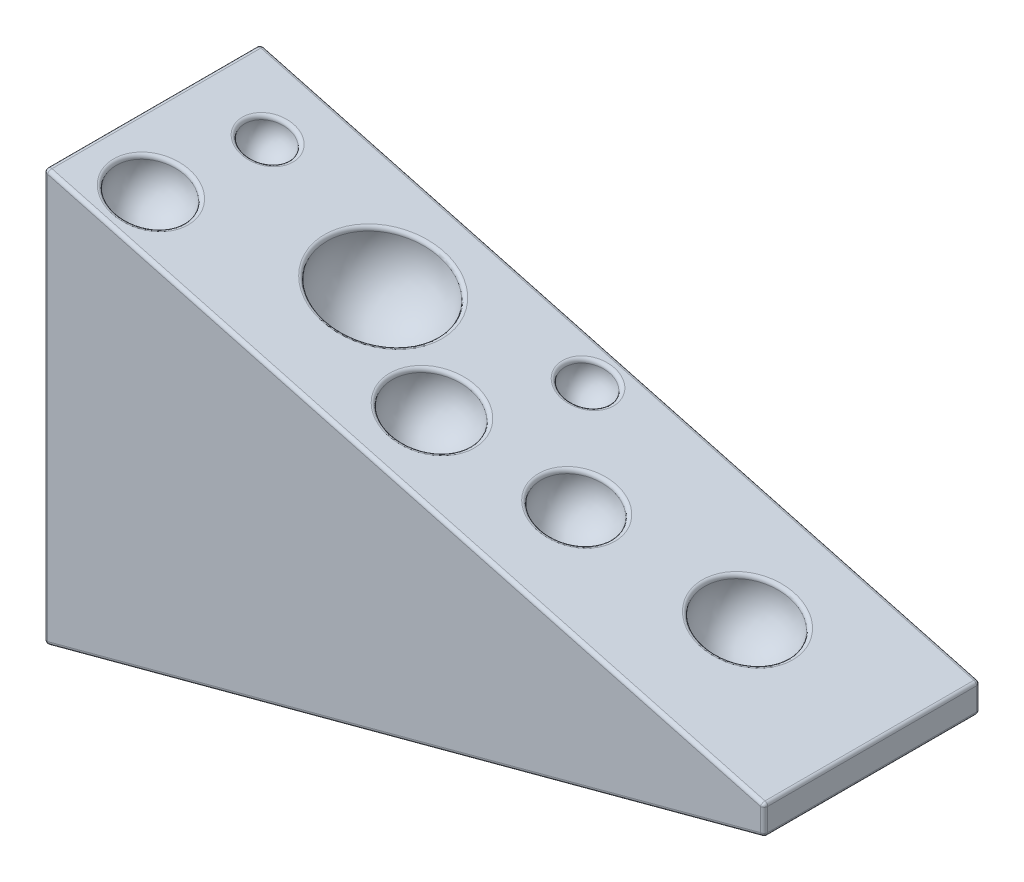
SolidWorks part; units mm, degrees
ref_plane "Front Plane" through (0, 0, 0) normal (0, 0, 1) x (1, 0, 0)
ref_plane "Top Plane" through (0, 0, 0) normal (0, 1, 0) x (1, 0, 0)
ref_plane "Right Plane" through (0, 0, 0) normal (1, 0, 0) x (0, 0, -1)
sketch "Sketch1" plane through (0, 0, 0) normal (0, 0, 1) x (1, 0, 0)
  line L0 (-975.3379, 57.5) -> (49024.6621, 57.5) construction
  line L1 (0, 0) -> (200, 53.5898)
  line L2 (0, 0) -> (0, 115)
  line L3 (0, 115) -> (200, 61.4102)
  line L4 (200, 53.5898) -> (200, 61.4102)
  point P7 (200, 57.5)
  dimension "D1" = 200
  dimension "D2" = 30
  dimension "D3" = 115
  dimension "D4" = 57.5
extrude "Boss-Extrude1" add sketch "Sketch1" along normal blind 60
sketch "Sketch2" plane through (0, 0, 0) normal (0.2588, -0.9659, 0) x (0.9659, 0.2588, 0)
  line L0 (117.0552, 35) -> (137.0552, 35) construction
  line L1 (0, 60) -> (207.0552, 60) construction
  line L2 (207.0552, 60) -> (207.0552, 0) construction
  line L3 (117.0552, 35) -> (137.0552, 35)
  arc A0 (137.0552, 35) -> (117.0552, 35) centre (127.0552, 35) ccw
  dimension "D1" = 10
  dimension "D2" = 25
  dimension "D3" = 80
revolve "Cut-Revolve1" cut sketch "Sketch2" angle 360 about L0
sketch "Sketch4" plane through (0, 0, 0) normal (0.2588, -0.9659, 0) x (0.9659, 0.2588, 0)
  line L0 (7.0994, 46.7676) -> (26.5364, 46.7676)
  arc A0 (26.5364, 46.7676) -> (7.0994, 46.7676) centre (16.8179, 46.7676) ccw
revolve "Cut-Revolve2" cut sketch "Sketch4" angle 360 about L0
sketch "Sketch5" plane through (0, 0, 0) normal (0.2588, -0.9659, 0) x (0.9659, 0.2588, 0)
  line L0 (45.8757, 25.6804) -> (77.6549, 25.6804)
  arc A0 (77.6549, 25.6804) -> (45.8757, 25.6804) centre (61.7653, 25.6804) ccw
revolve "Cut-Revolve3" cut sketch "Sketch5" angle 360 about L0
sketch "Sketch6" plane through (0, 0, 0) normal (0.2588, -0.9659, 0) x (0.9659, 0.2588, 0)
  line L0 (156.4971, 27.6063) -> (180.4971, 27.6063)
  arc A0 (180.4971, 27.6063) -> (156.4971, 27.6063) centre (168.4971, 27.6063) ccw
  dimension "D1" = 24
revolve "Cut-Revolve4" cut sketch "Sketch6" angle 360 about L0
sketch "Sketch7" plane through (0, 0, 0) normal (0.2588, -0.9659, 0) x (0.9659, 0.2588, 0)
  line L0 (13.4951, 17.2284) -> (26.0888, 17.2284)
  arc A0 (26.0888, 17.2284) -> (13.4951, 17.2284) centre (19.7919, 17.2284) ccw
revolve "Cut-Revolve5" cut sketch "Sketch7" angle 360 about L0
sketch "Sketch8" plane through (0, 0, 0) normal (0.2588, -0.9659, 0) x (0.9659, 0.2588, 0)
  line L0 (97.5898, 9.5515) -> (110.3086, 9.5515)
  arc A0 (110.3086, 9.5515) -> (97.5898, 9.5515) centre (103.9492, 9.5515) ccw
revolve "Cut-Revolve6" cut sketch "Sketch8" angle 360 about L0
sketch "Sketch9" plane through (0, 0, 0) normal (0.2588, -0.9659, 0) x (0.9659, 0.2588, 0)
  line L0 (80.4765, 40.977) -> (102.7844, 40.977)
  arc A0 (102.7844, 40.977) -> (80.4765, 40.977) centre (91.6305, 40.977) ccw
revolve "Cut-Revolve7" cut sketch "Sketch9" angle 360 about L0
ref_plane "Plane1" through (0, 57, 0) normal (0, 1, 0) x (1, 0, 0)
mirror "Mirror2" about plane through (0, 57, 0) normal (0, 1, 0) of "Cut-Revolve7", "Cut-Revolve6", "Cut-Revolve5", "Cut-Revolve4", "Cut-Revolve3", "Cut-Revolve2", "Cut-Revolve1"
fillet "Fillet1" radius 1 26 edges at (200, 61.4102, 30) (100, 88.2051, 60) (0, 115, 30) (100, 88.2051, 0) (132.59, 79.4726, 35) (25.8357, 108.0773, 46.7676) (75.2305, 94.8421, 25.6804) (174.5592, 68.227, 27.6063) (25.3778, 108.2, 17.2284) (106.7287, 86.4021, 9.5515) (99.4916, 88.3413, 40.977) (0, 0, 30) (100, 26.7949, 60) (200, 53.5898, 30) (100, 26.7949, 0) (113.0667, 30.2961, 35) (6.8575, 1.8375, 46.7676) (44.3125, 11.8735, 25.6804) (151.1646, 40.5044, 27.6063) (13.0352, 3.4928, 17.2284) (94.2645, 25.2581, 9.5515) (77.7343, 20.8289, 40.977) (0, 57.5, 0) (0, 57.5, 60) (200, 57.5, 0) (200, 57.5, 60)
